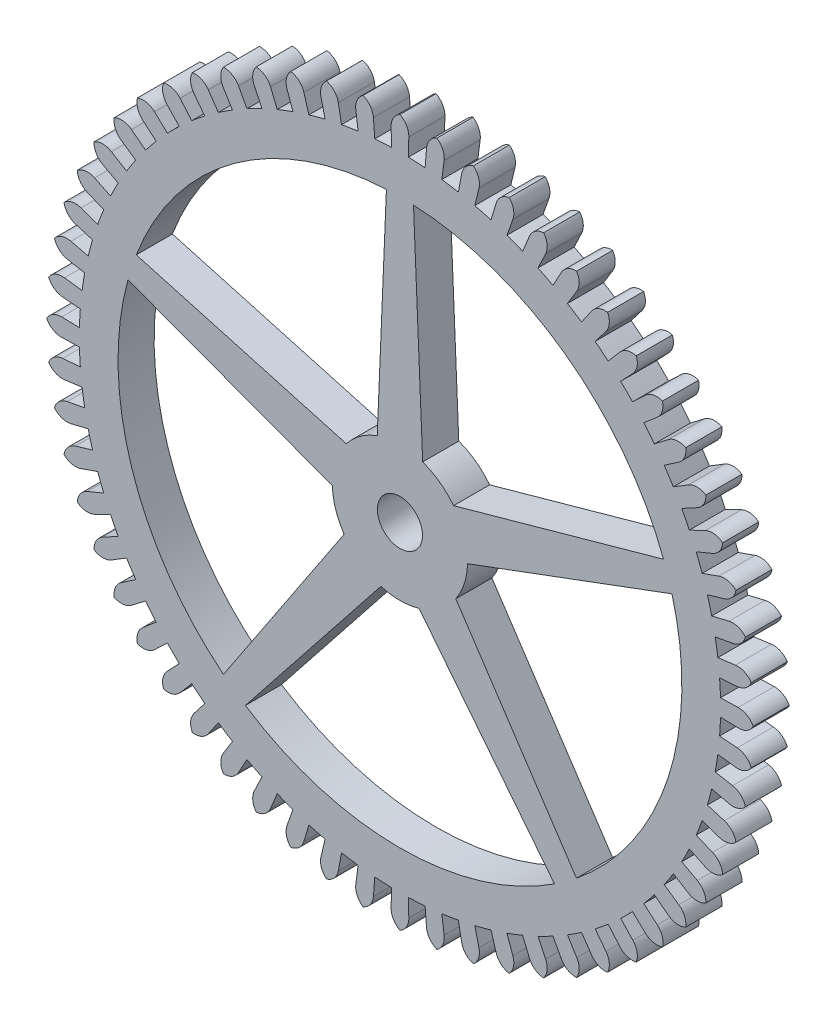
SolidWorks part; units mm, degrees
material "Brass"
ref_plane "Front Plane" through (0, 0, 0) normal (0, 0, 1) x (1, 0, 0)
ref_plane "Top Plane" through (0, 0, 0) normal (0, 1, 0) x (1, 0, 0)
ref_plane "Right Plane" through (0, 0, 0) normal (1, 0, 0) x (0, 0, -1)
sketch "Sketch1" plane through (0, 0, 0) normal (0, 0, 1) x (1, 0, 0)
  line L0 (0, -9.2996) -> (0, 10.099) construction
  line L1 (-0.1861, 7.1049) -> (-0.1963, 7.4974)
  line L2 (0.1861, 7.1049) -> (0.1963, 7.4974)
  line L3 (0.5576, 7.0854) -> (0.5884, 7.4769)
  line L4 (0.9277, 7.0465) -> (0.979, 7.4358)
  line L5 (1.2952, 6.9883) -> (1.3668, 7.3744)
  line L6 (1.6592, 6.9109) -> (1.7508, 7.2928)
  line L7 (2.0186, 6.8146) -> (2.1301, 7.1911)
  line L8 (2.3725, 6.6996) -> (2.5036, 7.0698)
  line L9 (2.7198, 6.5663) -> (2.8701, 6.9291)
  line L10 (3.0598, 6.4149) -> (3.2288, 6.7694)
  line L11 (3.3913, 6.246) -> (3.5787, 6.5911)
  line L12 (3.7136, 6.06) -> (3.9187, 6.3948)
  line L13 (4.0256, 5.8573) -> (4.248, 6.1809)
  line L14 (4.3267, 5.6386) -> (4.5657, 5.9501)
  line L15 (4.6158, 5.4044) -> (4.8709, 5.703)
  line L16 (4.8923, 5.1554) -> (5.1627, 5.4403)
  line L17 (5.1554, 4.8923) -> (5.4403, 5.1627)
  line L18 (5.4044, 4.6158) -> (5.703, 4.8709)
  line L19 (5.6386, 4.3267) -> (5.9501, 4.5657)
  line L20 (5.8573, 4.0256) -> (6.1809, 4.248)
  line L21 (6.06, 3.7136) -> (6.3948, 3.9187)
  line L22 (6.246, 3.3913) -> (6.5911, 3.5787)
  line L23 (6.4149, 3.0598) -> (6.7694, 3.2288)
  line L24 (6.5663, 2.7198) -> (6.9291, 2.8701)
  line L25 (6.6996, 2.3725) -> (7.0698, 2.5036)
  line L26 (6.8146, 2.0186) -> (7.1911, 2.1301)
  line L27 (6.9109, 1.6592) -> (7.2928, 1.7508)
  line L28 (6.9883, 1.2952) -> (7.3744, 1.3668)
  line L29 (7.0465, 0.9277) -> (7.4358, 0.979)
  line L30 (7.0854, 0.5576) -> (7.4769, 0.5884)
  line L31 (7.1049, 0.1861) -> (7.4974, 0.1963)
  line L32 (7.1049, -0.1861) -> (7.4974, -0.1963)
  line L33 (7.0854, -0.5576) -> (7.4769, -0.5884)
  line L34 (7.0465, -0.9277) -> (7.4358, -0.979)
  line L35 (6.9883, -1.2952) -> (7.3744, -1.3668)
  line L36 (6.9109, -1.6592) -> (7.2928, -1.7508)
  line L37 (6.8146, -2.0186) -> (7.1911, -2.1301)
  line L38 (6.6996, -2.3725) -> (7.0698, -2.5036)
  line L39 (6.5663, -2.7198) -> (6.9291, -2.8701)
  line L40 (6.4149, -3.0598) -> (6.7694, -3.2288)
  line L41 (6.246, -3.3913) -> (6.5911, -3.5787)
  line L42 (6.06, -3.7136) -> (6.3948, -3.9187)
  line L43 (5.8573, -4.0256) -> (6.1809, -4.248)
  line L44 (5.6386, -4.3267) -> (5.9501, -4.5657)
  line L45 (5.4044, -4.6158) -> (5.703, -4.8709)
  line L46 (5.1554, -4.8923) -> (5.4403, -5.1627)
  line L47 (4.8923, -5.1554) -> (5.1627, -5.4403)
  line L48 (4.6158, -5.4044) -> (4.8709, -5.703)
  line L49 (4.3267, -5.6386) -> (4.5657, -5.9501)
  line L50 (4.0256, -5.8573) -> (4.248, -6.1809)
  line L51 (3.7136, -6.06) -> (3.9187, -6.3948)
  line L52 (3.3913, -6.246) -> (3.5787, -6.5911)
  line L53 (3.0598, -6.4149) -> (3.2288, -6.7694)
  line L54 (2.7198, -6.5663) -> (2.8701, -6.9291)
  line L55 (2.3725, -6.6996) -> (2.5036, -7.0698)
  line L56 (2.0186, -6.8146) -> (2.1301, -7.1911)
  line L57 (1.6592, -6.9109) -> (1.7508, -7.2928)
  line L58 (1.2952, -6.9883) -> (1.3668, -7.3744)
  line L59 (0.9277, -7.0465) -> (0.979, -7.4358)
  line L60 (0.5576, -7.0854) -> (0.5884, -7.4769)
  line L61 (0.1861, -7.1049) -> (0.1963, -7.4974)
  line L62 (-0.1861, -7.1049) -> (-0.1963, -7.4974)
  line L63 (-0.5576, -7.0854) -> (-0.5884, -7.4769)
  line L64 (-0.9277, -7.0465) -> (-0.979, -7.4358)
  line L65 (-1.2952, -6.9883) -> (-1.3668, -7.3744)
  line L66 (-1.6592, -6.9109) -> (-1.7508, -7.2928)
  line L67 (-2.0186, -6.8146) -> (-2.1301, -7.1911)
  line L68 (-2.3725, -6.6996) -> (-2.5036, -7.0698)
  line L69 (-2.7198, -6.5663) -> (-2.8701, -6.9291)
  line L70 (-3.0598, -6.4149) -> (-3.2288, -6.7694)
  line L71 (-3.3913, -6.246) -> (-3.5787, -6.5911)
  line L72 (-3.7136, -6.06) -> (-3.9187, -6.3948)
  line L73 (-4.0256, -5.8573) -> (-4.248, -6.1809)
  line L74 (-4.3267, -5.6386) -> (-4.5657, -5.9501)
  line L75 (-4.6158, -5.4044) -> (-4.8709, -5.703)
  line L76 (-4.8923, -5.1554) -> (-5.1627, -5.4403)
  line L77 (-5.1554, -4.8923) -> (-5.4403, -5.1627)
  line L78 (-5.4044, -4.6158) -> (-5.703, -4.8709)
  line L79 (-5.6386, -4.3267) -> (-5.9501, -4.5657)
  line L80 (-5.8573, -4.0256) -> (-6.1809, -4.248)
  line L81 (-6.06, -3.7136) -> (-6.3948, -3.9187)
  line L82 (-6.246, -3.3913) -> (-6.5911, -3.5787)
  line L83 (-6.4149, -3.0598) -> (-6.7694, -3.2288)
  line L84 (-6.5663, -2.7198) -> (-6.9291, -2.8701)
  line L85 (-6.6996, -2.3725) -> (-7.0698, -2.5036)
  line L86 (-6.8146, -2.0186) -> (-7.1911, -2.1301)
  line L87 (-6.9109, -1.6592) -> (-7.2928, -1.7508)
  line L88 (-6.9883, -1.2952) -> (-7.3744, -1.3668)
  line L89 (-7.0465, -0.9277) -> (-7.4358, -0.979)
  line L90 (-7.0854, -0.5576) -> (-7.4769, -0.5884)
  line L91 (-7.1049, -0.1861) -> (-7.4974, -0.1963)
  line L92 (-7.1049, 0.1861) -> (-7.4974, 0.1963)
  line L93 (-7.0854, 0.5576) -> (-7.4769, 0.5884)
  line L94 (-7.0465, 0.9277) -> (-7.4358, 0.979)
  line L95 (-6.9883, 1.2952) -> (-7.3744, 1.3668)
  line L96 (-6.9109, 1.6592) -> (-7.2928, 1.7508)
  line L97 (-6.8146, 2.0186) -> (-7.1911, 2.1301)
  line L98 (-6.6996, 2.3725) -> (-7.0698, 2.5036)
  line L99 (-6.5663, 2.7198) -> (-6.9291, 2.8701)
  line L100 (-6.4149, 3.0598) -> (-6.7694, 3.2288)
  line L101 (-6.246, 3.3913) -> (-6.5911, 3.5787)
  line L102 (-6.06, 3.7136) -> (-6.3948, 3.9187)
  line L103 (-5.8573, 4.0256) -> (-6.1809, 4.248)
  line L104 (-5.6386, 4.3267) -> (-5.9501, 4.5657)
  line L105 (-5.4044, 4.6158) -> (-5.703, 4.8709)
  line L106 (-5.1554, 4.8923) -> (-5.4403, 5.1627)
  line L107 (-4.8923, 5.1554) -> (-5.1627, 5.4403)
  line L108 (-4.6158, 5.4044) -> (-4.8709, 5.703)
  line L109 (-4.3267, 5.6386) -> (-4.5657, 5.9501)
  line L110 (-4.0256, 5.8573) -> (-4.248, 6.1809)
  line L111 (-3.7136, 6.06) -> (-3.9187, 6.3948)
  line L112 (-3.3913, 6.246) -> (-3.5787, 6.5911)
  line L113 (-3.0598, 6.4149) -> (-3.2288, 6.7694)
  line L114 (-2.7198, 6.5663) -> (-2.8701, 6.9291)
  line L115 (-2.3725, 6.6996) -> (-2.5036, 7.0698)
  line L116 (-2.0186, 6.8146) -> (-2.1301, 7.1911)
  line L117 (-1.6592, 6.9109) -> (-1.7508, 7.2928)
  line L118 (-1.2952, 6.9883) -> (-1.3668, 7.3744)
  line L119 (-0.9277, 7.0465) -> (-0.979, 7.4358)
  line L120 (-0.5576, 7.0854) -> (-0.5884, 7.4769)
  line L121 (-0.3, 6.25) -> (-0.5037, 1.4129)
  line L122 (0.5037, 1.4129) -> (0.3, 6.25)
  line L123 (5.8514, 2.2167) -> (1.1881, 0.9156)
  line L124 (1.4994, -0.0424) -> (6.0368, 1.646)
  line L125 (3.9164, -4.88) -> (1.238, -0.847)
  line L126 (0.423, -1.4391) -> (3.431, -5.2327)
  line L127 (-3.431, -5.2327) -> (-0.423, -1.4391)
  line L128 (-1.238, -0.847) -> (-3.9164, -4.88)
  line L129 (-6.0368, 1.646) -> (-1.4994, -0.0424)
  line L130 (-1.1881, 0.9156) -> (-5.8514, 2.2167)
  arc A0 (-0.9277, 7.0465) -> (-1.2952, 6.9883) centre (0, 0) ccw
  arc A1 (0.5576, 7.0854) -> (0.1861, 7.1049) centre (0, 0) ccw
  arc A2 (-0.1861, 7.1049) -> (-0.5576, 7.0854) centre (0, 0) ccw
  arc A3 (0.979, 7.4358) -> (0.8185, 7.7878) centre (0.6171, 7.4835) ccw
  arc A4 (-0.1963, 7.4974) -> (0, 7.8307) centre (0.1685, 7.507) cw
  arc A5 (0.1963, 7.4974) -> (0, 7.8307) centre (-0.1685, 7.507) ccw
  arc A6 (0.5884, 7.4769) -> (0.8185, 7.7878) centre (0.9522, 7.4482) cw
  arc A7 (1.7508, 7.2928) -> (1.6281, 7.6596) centre (1.396, 7.378) ccw
  arc A8 (1.3668, 7.3744) -> (1.6281, 7.6596) centre (1.7256, 7.3079) cw
  arc A9 (2.5036, 7.0698) -> (2.4198, 7.4474) centre (2.1596, 7.1916) ccw
  arc A10 (2.1301, 7.1911) -> (2.4198, 7.4474) centre (2.48, 7.0875) cw
  arc A11 (3.2288, 6.7694) -> (3.185, 7.1537) centre (2.8995, 6.9265) ccw
  arc A12 (2.8701, 6.9291) -> (3.185, 7.1537) centre (3.2073, 6.7894) cw
  arc A13 (3.9187, 6.3948) -> (3.9154, 6.7816) centre (3.6076, 6.5855) ccw
  arc A14 (3.5787, 6.5911) -> (3.9154, 6.7816) centre (3.8994, 6.417) cw
  arc A15 (4.5657, 5.9501) -> (4.6028, 6.3352) centre (4.2762, 6.1723) ccw
  arc A16 (4.248, 6.1809) -> (4.6028, 6.3352) centre (4.5488, 5.9742) cw
  arc A17 (5.1627, 5.4403) -> (5.2398, 5.8193) centre (4.898, 5.6915) ccw
  arc A18 (4.8709, 5.703) -> (5.2398, 5.8193) centre (5.1484, 5.466) cw
  arc A19 (5.703, 4.8709) -> (5.8193, 5.2398) centre (5.466, 5.1484) ccw
  arc A20 (5.4403, 5.1627) -> (5.8193, 5.2398) centre (5.6915, 4.898) cw
  arc A21 (6.1809, 4.248) -> (6.3352, 4.6028) centre (5.9742, 4.5488) ccw
  arc A22 (5.9501, 4.5657) -> (6.3352, 4.6028) centre (6.1723, 4.2762) cw
  arc A23 (6.5911, 3.5787) -> (6.7816, 3.9154) centre (6.417, 3.8994) ccw
  arc A24 (6.3948, 3.9187) -> (6.7816, 3.9154) centre (6.5855, 3.6076) cw
  arc A25 (6.9291, 2.8701) -> (7.1537, 3.185) centre (6.7894, 3.2073) ccw
  arc A26 (6.7694, 3.2288) -> (7.1537, 3.185) centre (6.9265, 2.8995) cw
  arc A27 (7.1911, 2.1301) -> (7.4474, 2.4198) centre (7.0875, 2.48) ccw
  arc A28 (7.0698, 2.5036) -> (7.4474, 2.4198) centre (7.1916, 2.1596) cw
  arc A29 (7.3744, 1.3668) -> (7.6596, 1.6281) centre (7.3079, 1.7256) ccw
  arc A30 (7.2928, 1.7508) -> (7.6596, 1.6281) centre (7.378, 1.396) cw
  arc A31 (7.4769, 0.5884) -> (7.7878, 0.8185) centre (7.4482, 0.9522) ccw
  arc A32 (7.4358, 0.979) -> (7.7878, 0.8185) centre (7.4835, 0.6171) cw
  arc A33 (7.4974, -0.1963) -> (7.8307, 0) centre (7.507, 0.1685) ccw
  arc A34 (7.4974, 0.1963) -> (7.8307, 0) centre (7.507, -0.1685) cw
  arc A35 (7.4358, -0.979) -> (7.7878, -0.8185) centre (7.4835, -0.6171) ccw
  arc A36 (7.4769, -0.5884) -> (7.7878, -0.8185) centre (7.4482, -0.9522) cw
  arc A37 (7.2928, -1.7508) -> (7.6596, -1.6281) centre (7.378, -1.396) ccw
  arc A38 (7.3744, -1.3668) -> (7.6596, -1.6281) centre (7.3079, -1.7256) cw
  arc A39 (7.0698, -2.5036) -> (7.4474, -2.4198) centre (7.1916, -2.1596) ccw
  arc A40 (7.1911, -2.1301) -> (7.4474, -2.4198) centre (7.0875, -2.48) cw
  arc A41 (6.7694, -3.2288) -> (7.1537, -3.185) centre (6.9265, -2.8995) ccw
  arc A42 (6.9291, -2.8701) -> (7.1537, -3.185) centre (6.7894, -3.2073) cw
  arc A43 (6.3948, -3.9187) -> (6.7816, -3.9154) centre (6.5855, -3.6076) ccw
  arc A44 (6.5911, -3.5787) -> (6.7816, -3.9154) centre (6.417, -3.8994) cw
  arc A45 (5.9501, -4.5657) -> (6.3352, -4.6028) centre (6.1723, -4.2762) ccw
  arc A46 (6.1809, -4.248) -> (6.3352, -4.6028) centre (5.9742, -4.5488) cw
  arc A47 (5.4403, -5.1627) -> (5.8193, -5.2398) centre (5.6915, -4.898) ccw
  arc A48 (5.703, -4.8709) -> (5.8193, -5.2398) centre (5.466, -5.1484) cw
  arc A49 (4.8709, -5.703) -> (5.2398, -5.8193) centre (5.1484, -5.466) ccw
  arc A50 (5.1627, -5.4403) -> (5.2398, -5.8193) centre (4.898, -5.6915) cw
  arc A51 (4.248, -6.1809) -> (4.6028, -6.3352) centre (4.5488, -5.9742) ccw
  arc A52 (4.5657, -5.9501) -> (4.6028, -6.3352) centre (4.2762, -6.1723) cw
  arc A53 (3.5787, -6.5911) -> (3.9154, -6.7816) centre (3.8994, -6.417) ccw
  arc A54 (3.9187, -6.3948) -> (3.9154, -6.7816) centre (3.6076, -6.5855) cw
  arc A55 (2.8701, -6.9291) -> (3.185, -7.1537) centre (3.2073, -6.7894) ccw
  arc A56 (3.2288, -6.7694) -> (3.185, -7.1537) centre (2.8995, -6.9265) cw
  arc A57 (2.1301, -7.1911) -> (2.4198, -7.4474) centre (2.48, -7.0875) ccw
  arc A58 (2.5036, -7.0698) -> (2.4198, -7.4474) centre (2.1596, -7.1916) cw
  arc A59 (1.3668, -7.3744) -> (1.6281, -7.6596) centre (1.7256, -7.3079) ccw
  arc A60 (1.7508, -7.2928) -> (1.6281, -7.6596) centre (1.396, -7.378) cw
  arc A61 (0.5884, -7.4769) -> (0.8185, -7.7878) centre (0.9522, -7.4482) ccw
  arc A62 (0.979, -7.4358) -> (0.8185, -7.7878) centre (0.6171, -7.4835) cw
  arc A63 (-0.1963, -7.4974) -> (0, -7.8307) centre (0.1685, -7.507) ccw
  arc A64 (0.1963, -7.4974) -> (0, -7.8307) centre (-0.1685, -7.507) cw
  arc A65 (-0.979, -7.4358) -> (-0.8185, -7.7878) centre (-0.6171, -7.4835) ccw
  arc A66 (-0.5884, -7.4769) -> (-0.8185, -7.7878) centre (-0.9522, -7.4482) cw
  arc A67 (-1.7508, -7.2928) -> (-1.6281, -7.6596) centre (-1.396, -7.378) ccw
  arc A68 (-1.3668, -7.3744) -> (-1.6281, -7.6596) centre (-1.7256, -7.3079) cw
  arc A69 (-2.5036, -7.0698) -> (-2.4198, -7.4474) centre (-2.1596, -7.1916) ccw
  arc A70 (-2.1301, -7.1911) -> (-2.4198, -7.4474) centre (-2.48, -7.0875) cw
  arc A71 (-3.2288, -6.7694) -> (-3.185, -7.1537) centre (-2.8995, -6.9265) ccw
  arc A72 (-2.8701, -6.9291) -> (-3.185, -7.1537) centre (-3.2073, -6.7894) cw
  arc A73 (-3.9187, -6.3948) -> (-3.9154, -6.7816) centre (-3.6076, -6.5855) ccw
  arc A74 (-3.5787, -6.5911) -> (-3.9154, -6.7816) centre (-3.8994, -6.417) cw
  arc A75 (-4.5657, -5.9501) -> (-4.6028, -6.3352) centre (-4.2762, -6.1723) ccw
  arc A76 (-4.248, -6.1809) -> (-4.6028, -6.3352) centre (-4.5488, -5.9742) cw
  arc A77 (-5.1627, -5.4403) -> (-5.2398, -5.8193) centre (-4.898, -5.6915) ccw
  arc A78 (-4.8709, -5.703) -> (-5.2398, -5.8193) centre (-5.1484, -5.466) cw
  arc A79 (-5.703, -4.8709) -> (-5.8193, -5.2398) centre (-5.466, -5.1484) ccw
  arc A80 (-5.4403, -5.1627) -> (-5.8193, -5.2398) centre (-5.6915, -4.898) cw
  arc A81 (-6.1809, -4.248) -> (-6.3352, -4.6028) centre (-5.9742, -4.5488) ccw
  arc A82 (-5.9501, -4.5657) -> (-6.3352, -4.6028) centre (-6.1723, -4.2762) cw
  arc A83 (-6.5911, -3.5787) -> (-6.7816, -3.9154) centre (-6.417, -3.8994) ccw
  arc A84 (-6.3948, -3.9187) -> (-6.7816, -3.9154) centre (-6.5855, -3.6076) cw
  arc A85 (-6.9291, -2.8701) -> (-7.1537, -3.185) centre (-6.7894, -3.2073) ccw
  arc A86 (-6.7694, -3.2288) -> (-7.1537, -3.185) centre (-6.9265, -2.8995) cw
  arc A87 (-7.1911, -2.1301) -> (-7.4474, -2.4198) centre (-7.0875, -2.48) ccw
  arc A88 (-7.0698, -2.5036) -> (-7.4474, -2.4198) centre (-7.1916, -2.1596) cw
  arc A89 (-7.3744, -1.3668) -> (-7.6596, -1.6281) centre (-7.3079, -1.7256) ccw
  arc A90 (-7.2928, -1.7508) -> (-7.6596, -1.6281) centre (-7.378, -1.396) cw
  arc A91 (-7.4769, -0.5884) -> (-7.7878, -0.8185) centre (-7.4482, -0.9522) ccw
  arc A92 (-7.4358, -0.979) -> (-7.7878, -0.8185) centre (-7.4835, -0.6171) cw
  arc A93 (-7.4974, 0.1963) -> (-7.8307, 0) centre (-7.507, -0.1685) ccw
  arc A94 (-7.4974, -0.1963) -> (-7.8307, 0) centre (-7.507, 0.1685) cw
  arc A95 (-7.4358, 0.979) -> (-7.7878, 0.8185) centre (-7.4835, 0.6171) ccw
  arc A96 (-7.4769, 0.5884) -> (-7.7878, 0.8185) centre (-7.4482, 0.9522) cw
  arc A97 (-7.2928, 1.7508) -> (-7.6596, 1.6281) centre (-7.378, 1.396) ccw
  arc A98 (-7.3744, 1.3668) -> (-7.6596, 1.6281) centre (-7.3079, 1.7256) cw
  arc A99 (-7.0698, 2.5036) -> (-7.4474, 2.4198) centre (-7.1916, 2.1596) ccw
  arc A100 (-7.1911, 2.1301) -> (-7.4474, 2.4198) centre (-7.0875, 2.48) cw
  arc A101 (-6.7694, 3.2288) -> (-7.1537, 3.185) centre (-6.9265, 2.8995) ccw
  arc A102 (-6.9291, 2.8701) -> (-7.1537, 3.185) centre (-6.7894, 3.2073) cw
  arc A103 (-6.3948, 3.9187) -> (-6.7816, 3.9154) centre (-6.5855, 3.6076) ccw
  arc A104 (-6.5911, 3.5787) -> (-6.7816, 3.9154) centre (-6.417, 3.8994) cw
  arc A105 (-5.9501, 4.5657) -> (-6.3352, 4.6028) centre (-6.1723, 4.2762) ccw
  arc A106 (-6.1809, 4.248) -> (-6.3352, 4.6028) centre (-5.9742, 4.5488) cw
  arc A107 (-5.4403, 5.1627) -> (-5.8193, 5.2398) centre (-5.6915, 4.898) ccw
  arc A108 (-5.703, 4.8709) -> (-5.8193, 5.2398) centre (-5.466, 5.1484) cw
  arc A109 (-4.8709, 5.703) -> (-5.2398, 5.8193) centre (-5.1484, 5.466) ccw
  arc A110 (-5.1627, 5.4403) -> (-5.2398, 5.8193) centre (-4.898, 5.6915) cw
  arc A111 (-4.248, 6.1809) -> (-4.6028, 6.3352) centre (-4.5488, 5.9742) ccw
  arc A112 (-4.5657, 5.9501) -> (-4.6028, 6.3352) centre (-4.2762, 6.1723) cw
  arc A113 (-3.5787, 6.5911) -> (-3.9154, 6.7816) centre (-3.8994, 6.417) ccw
  arc A114 (-3.9187, 6.3948) -> (-3.9154, 6.7816) centre (-3.6076, 6.5855) cw
  arc A115 (-2.8701, 6.9291) -> (-3.185, 7.1537) centre (-3.2073, 6.7894) ccw
  arc A116 (-3.2288, 6.7694) -> (-3.185, 7.1537) centre (-2.8995, 6.9265) cw
  arc A117 (-2.1301, 7.1911) -> (-2.4198, 7.4474) centre (-2.48, 7.0875) ccw
  arc A118 (-2.5036, 7.0698) -> (-2.4198, 7.4474) centre (-2.1596, 7.1916) cw
  arc A119 (-1.3668, 7.3744) -> (-1.6281, 7.6596) centre (-1.7256, 7.3079) ccw
  arc A120 (-1.7508, 7.2928) -> (-1.6281, 7.6596) centre (-1.396, 7.378) cw
  arc A121 (-0.5884, 7.4769) -> (-0.8185, 7.7878) centre (-0.9522, 7.4482) ccw
  arc A122 (-0.979, 7.4358) -> (-0.8185, 7.7878) centre (-0.6171, 7.4835) cw
  arc A123 (1.2952, 6.9883) -> (0.9277, 7.0465) centre (0, 0) ccw
  arc A124 (2.0186, 6.8146) -> (1.6592, 6.9109) centre (0, 0) ccw
  arc A125 (2.7198, 6.5663) -> (2.3725, 6.6996) centre (0, 0) ccw
  arc A126 (-1.6592, 6.9109) -> (-2.0186, 6.8146) centre (0, 0) ccw
  arc A127 (-2.3725, 6.6996) -> (-2.7198, 6.5663) centre (0, 0) ccw
  arc A128 (-3.0598, 6.4149) -> (-3.3913, 6.246) centre (0, 0) ccw
  arc A129 (-3.7136, 6.06) -> (-4.0256, 5.8573) centre (0, 0) ccw
  arc A130 (-4.3267, 5.6386) -> (-4.6158, 5.4044) centre (0, 0) ccw
  arc A131 (-4.8923, 5.1554) -> (-5.1554, 4.8923) centre (0, 0) ccw
  arc A132 (-5.4044, 4.6158) -> (-5.6386, 4.3267) centre (0, 0) ccw
  arc A133 (-5.8573, 4.0256) -> (-6.06, 3.7136) centre (0, 0) ccw
  arc A134 (-6.246, 3.3913) -> (-6.4149, 3.0598) centre (0, 0) ccw
  arc A135 (-6.5663, 2.7198) -> (-6.6996, 2.3725) centre (0, 0) ccw
  arc A136 (-6.8146, 2.0186) -> (-6.9109, 1.6592) centre (0, 0) ccw
  arc A137 (-6.9883, 1.2952) -> (-7.0465, 0.9277) centre (0, 0) ccw
  arc A138 (-7.0854, 0.5576) -> (-7.1049, 0.1861) centre (0, 0) ccw
  arc A139 (-7.1049, -0.1861) -> (-7.0854, -0.5576) centre (0, 0) ccw
  arc A140 (-7.0465, -0.9277) -> (-6.9883, -1.2952) centre (0, 0) ccw
  arc A141 (-6.9109, -1.6592) -> (-6.8146, -2.0186) centre (0, 0) ccw
  arc A142 (-6.6996, -2.3725) -> (-6.5663, -2.7198) centre (0, 0) ccw
  arc A143 (-6.4149, -3.0598) -> (-6.246, -3.3913) centre (0, 0) ccw
  arc A144 (-6.06, -3.7136) -> (-5.8573, -4.0256) centre (0, 0) ccw
  arc A145 (-5.6386, -4.3267) -> (-5.4044, -4.6158) centre (0, 0) ccw
  arc A146 (-5.1554, -4.8923) -> (-4.8923, -5.1554) centre (0, 0) ccw
  arc A147 (-4.6158, -5.4044) -> (-4.3267, -5.6386) centre (0, 0) ccw
  arc A148 (-4.0256, -5.8573) -> (-3.7136, -6.06) centre (0, 0) ccw
  arc A149 (-3.3913, -6.246) -> (-3.0598, -6.4149) centre (0, 0) ccw
  arc A150 (-2.7198, -6.5663) -> (-2.3725, -6.6996) centre (0, 0) ccw
  arc A151 (-2.0186, -6.8146) -> (-1.6592, -6.9109) centre (0, 0) ccw
  arc A152 (-1.2952, -6.9883) -> (-0.9277, -7.0465) centre (0, 0) ccw
  arc A153 (-0.5576, -7.0854) -> (-0.1861, -7.1049) centre (0, 0) ccw
  arc A154 (0.1861, -7.1049) -> (0.5576, -7.0854) centre (0, 0) ccw
  arc A155 (0.9277, -7.0465) -> (1.2952, -6.9883) centre (0, 0) ccw
  arc A156 (1.6592, -6.9109) -> (2.0186, -6.8146) centre (0, 0) ccw
  arc A157 (2.3725, -6.6996) -> (2.7198, -6.5663) centre (0, 0) ccw
  arc A158 (3.0598, -6.4149) -> (3.3913, -6.246) centre (0, 0) ccw
  arc A159 (3.7136, -6.06) -> (4.0256, -5.8573) centre (0, 0) ccw
  arc A160 (4.3267, -5.6386) -> (4.6158, -5.4044) centre (0, 0) ccw
  arc A161 (4.8923, -5.1554) -> (5.1554, -4.8923) centre (0, 0) ccw
  arc A162 (5.4044, -4.6158) -> (5.6386, -4.3267) centre (0, 0) ccw
  arc A163 (5.8573, -4.0256) -> (6.06, -3.7136) centre (0, 0) ccw
  arc A164 (6.246, -3.3913) -> (6.4149, -3.0598) centre (0, 0) ccw
  arc A165 (6.5663, -2.7198) -> (6.6996, -2.3725) centre (0, 0) ccw
  arc A166 (6.8146, -2.0186) -> (6.9109, -1.6592) centre (0, 0) ccw
  arc A167 (6.9883, -1.2952) -> (7.0465, -0.9277) centre (0, 0) ccw
  arc A168 (7.0854, -0.5576) -> (7.1049, -0.1861) centre (0, 0) ccw
  arc A169 (7.1049, 0.1861) -> (7.0854, 0.5576) centre (0, 0) ccw
  arc A170 (7.0465, 0.9277) -> (6.9883, 1.2952) centre (0, 0) ccw
  arc A171 (6.9109, 1.6592) -> (6.8146, 2.0186) centre (0, 0) ccw
  arc A172 (6.6996, 2.3725) -> (6.5663, 2.7198) centre (0, 0) ccw
  arc A173 (6.4149, 3.0598) -> (6.246, 3.3913) centre (0, 0) ccw
  arc A174 (6.06, 3.7136) -> (5.8573, 4.0256) centre (0, 0) ccw
  arc A175 (5.6386, 4.3267) -> (5.4044, 4.6158) centre (0, 0) ccw
  arc A176 (5.1554, 4.8923) -> (4.8923, 5.1554) centre (0, 0) ccw
  arc A177 (4.6158, 5.4044) -> (4.3267, 5.6386) centre (0, 0) ccw
  arc A178 (4.0256, 5.8573) -> (3.7136, 6.06) centre (0, 0) ccw
  arc A179 (3.3913, 6.246) -> (3.0598, 6.4149) centre (0, 0) ccw
  circle A180 centre (0, 0) radius 0.5
  circle A181 centre (0, 0) radius 1.5
  circle A182 centre (0, 0) radius 6.25
  point P429 (0, 0)
  point P450 (0, 0)
  dimension "D1" = 1
  dimension "D2" = 14.2146
  dimension "D3" = 3
  dimension "D4" = 60
  dimension "D5" = 12.5
  dimension "D6" = 5
  dimension "D7" = 15.6614
extrude "Boss-Extrude5" add sketch "Sketch1" against normal blind 0.8
